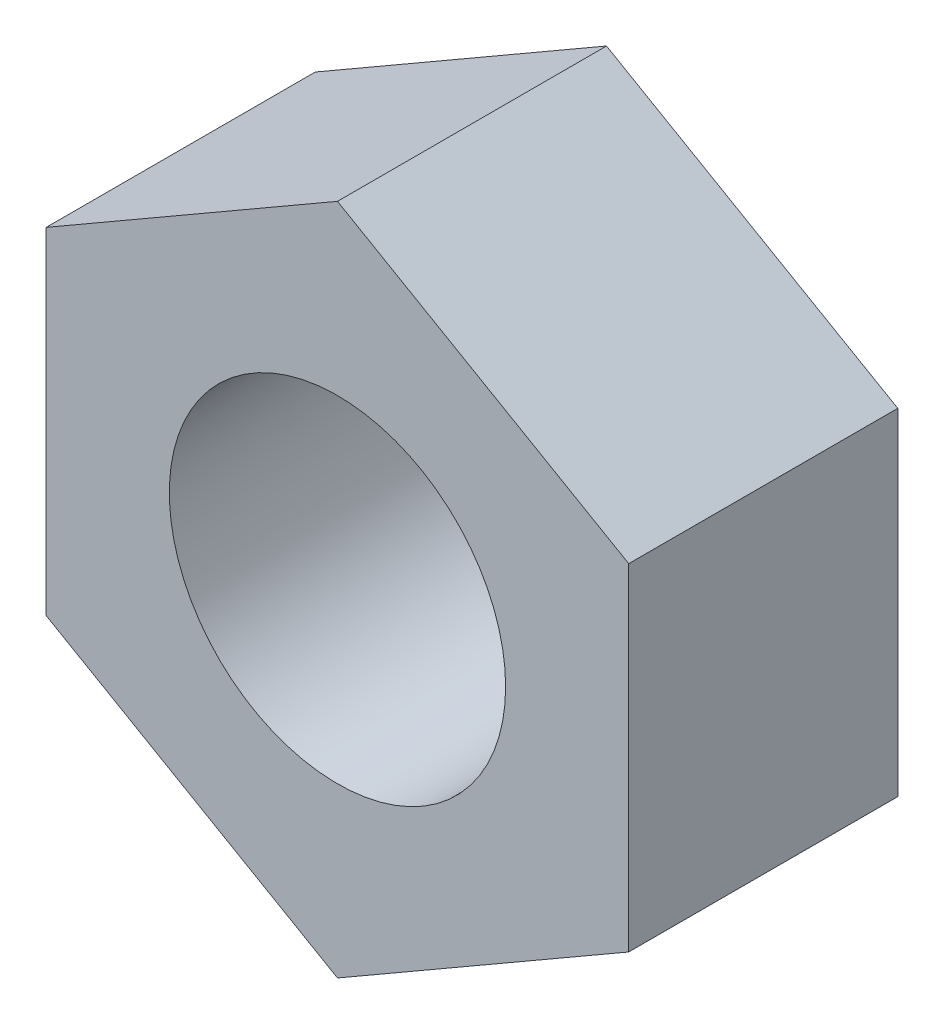
SolidWorks part; units mm, degrees
ref_plane "Přední rovina" through (0, 0, 0) normal (0, 0, 1) x (1, 0, 0)
ref_plane "Horní rovina" through (0, 0, 0) normal (0, 1, 0) x (1, 0, 0)
ref_plane "Pravá rovina" through (0, 0, 0) normal (1, 0, 0) x (0, 0, -1)
sketch "Skica1" plane through (0, 0, 0) normal (0, 0, 1) x (1, 0, 0)
  line L1 (0, 6) -> (-5.1962, 3)
  line L2 (-5.1962, 3) -> (-5.1962, -3)
  line L3 (-5.1962, -3) -> (0, -6)
  line L4 (0, -6) -> (5.1962, -3)
  line L5 (5.1962, -3) -> (5.1962, 3)
  line L6 (5.1962, 3) -> (0, 6)
  circle A0 centre (0, 0) radius 3
  circle A1 centre (0, 0) radius 5.1962 construction
  dimension "D1" = 6
  dimension "D2" = 12
extrude "Přidat vysunutím1" add sketch "Skica1" along normal blind 4.8
